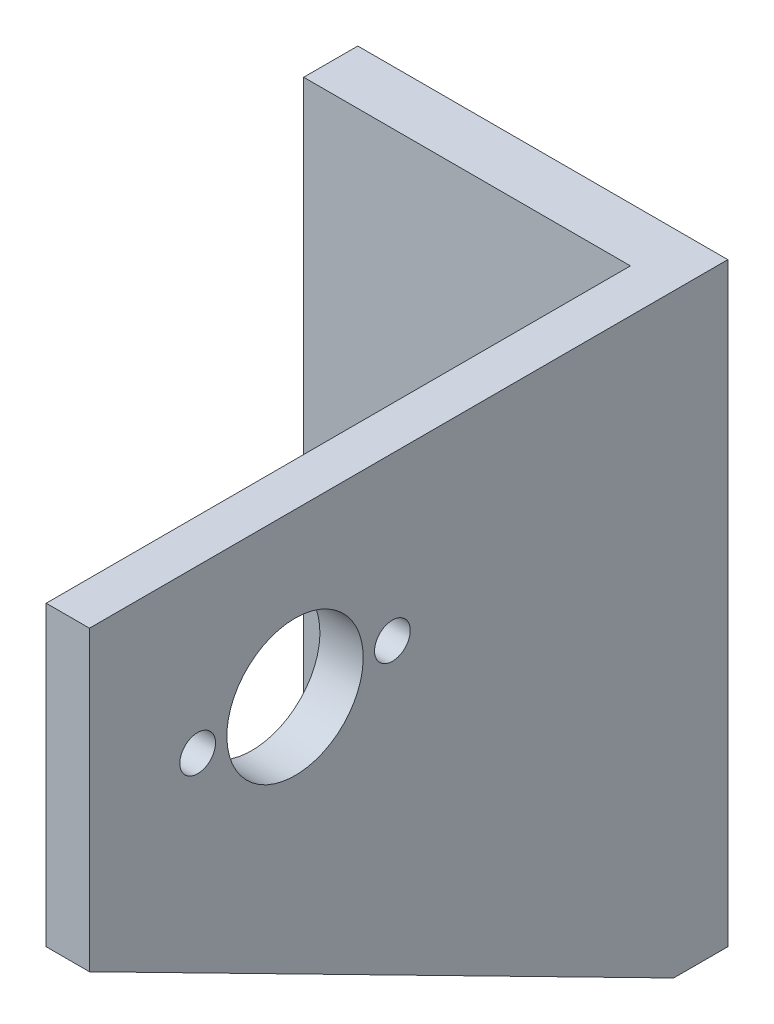
SolidWorks part; units mm, degrees
ref_plane "前视基准面" through (0, 0, 0) normal (0, 0, 1) x (1, 0, 0)
ref_plane "上视基准面" through (0, 0, 0) normal (0, 1, 0) x (1, 0, 0)
ref_plane "右视基准面" through (0, 0, 0) normal (1, 0, 0) x (0, 0, -1)
sketch "草图2" plane through (0, 0, 0) normal (0, 0, 1) x (1, 0, 0)
  line L0 (0, -5) -> (0, 35)
  line L1 (-15.6, 35) -> (-15.6, -5)
  line L2 (18.6, 35) -> (18.6, -20)
  line L3 (15.6, 0) -> (15.6, 35)
  line L4 (15.6, 35) -> (15.6, 0)
  line L5 (15.6, 35) -> (18.6, 35)
  line L7 (-15.6, -5) -> (-15.6, -20)
  line L8 (18.6, 35) -> (-15.6, 35)
  line L15 (-15.6, -20) -> (18.6, -20)
  circle A1 centre (0, -5) radius 12.6
  circle A2 centre (9, -5) radius 1.65
  circle A3 centre (-9, -5) radius 1.65
  circle A5 centre (0, -5) radius 6.3
extrude "凸台-拉伸1" add sketch "草图2" along normal blind 5
sketch "草图4" plane through (0, 0, 5) normal (0, 0, 1) x (1, 0, 0)
  line L0 (18.6, 35) -> (18.6, -20)
  line L1 (18.6, 35) -> (14.6, 35)
  line L2 (18.6, -20) -> (14.6, -20)
  line L3 (14.6, 35) -> (14.6, -20)
extrude "凸台-拉伸3" add sketch "草图4" along normal blind 54
sketch "草图6" plane through (0, 0, 0) normal (1, 0, 0) x (0, 0, -1)
  line L0 (-59, 35) -> (0, 35)
  line L1 (-59, 35) -> (-59, 20)
  line L2 (0, 35) -> (0, 20)
  line L3 (-59, 20) -> (0, 20)
  line L4 (0, -20) -> (-5, -20)
  line L5 (-59, -20) -> (0, -20) construction
  line L6 (-59, 7.5) -> (-5, -20)
  line L7 (-59, -20) -> (-59, 35) construction
  line L8 (-59, 7.5) -> (-59, -20)
  line L9 (-59, -20) -> (-5, -20)
  circle A2 centre (-49, 20) radius 1.65
  circle A3 centre (-31, 20) radius 1.65
  circle A5 centre (-40, 20) radius 6.3
extrude "切除-拉伸1" cut sketch "草图6" along normal blind 54 contours L8 L9 L6 | L3 A3 | L3 A3 | L3 A5 | L3 A5 | L3 A2 | L3 A2
